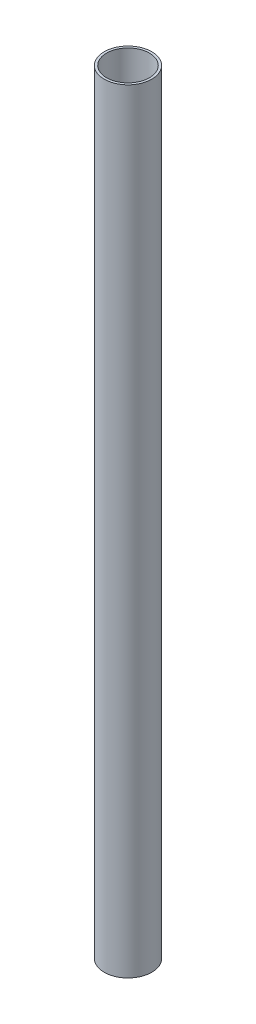
SolidWorks part; units mm, degrees
material "Thornel Mat VMA"
ref_plane "前视基准面" through (0, 0, 0) normal (0, 0, 1) x (1, 0, 0)
ref_plane "上视基准面" through (0, 0, 0) normal (0, 1, 0) x (1, 0, 0)
ref_plane "右视基准面" through (0, 0, 0) normal (1, 0, 0) x (0, 0, -1)
sketch "草图1" plane through (0, 0, 0) normal (0, 1, 0) x (1, 0, 0)
  circle A0 centre (0, 0) radius 10
  circle A1 centre (0, 0) radius 9
  dimension "D1" = 20
  dimension "D2" = 1
extrude "凸台-拉伸1" add sketch "草图1" along normal blind 325
